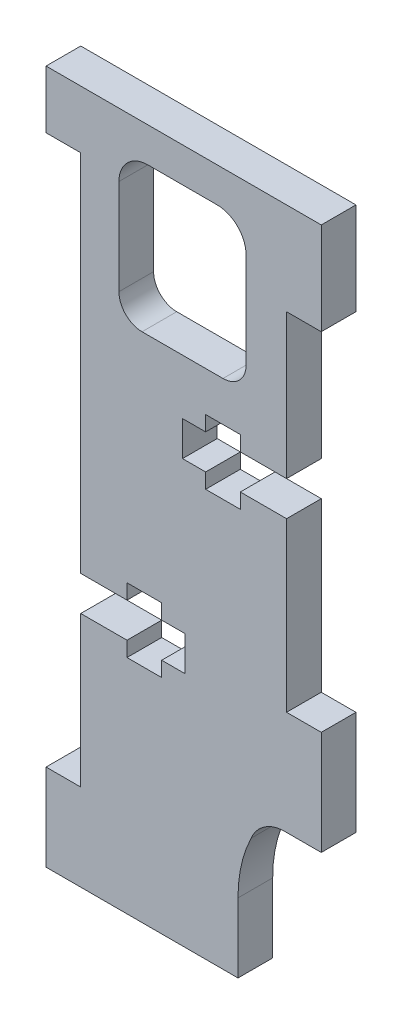
SolidWorks part; units mm, degrees
ref_plane "前基準面" through (0, 0, 0) normal (0, 0, 1) x (1, 0, 0)
ref_plane "上基準面" through (0, 0, 0) normal (0, 1, 0) x (1, 0, 0)
ref_plane "右基準面" through (0, 0, 0) normal (1, 0, 0) x (0, 0, -1)
sketch "草圖1" plane through (0, 0, 0) normal (0, 0, 1) x (1, 0, 0)
  line L0 (284.8002, 84.988) -> (278.8002, 84.988) construction
  line L1 (287.3002, 74.238) -> (287.3002, 82.488) construction
  line L2 (276.3002, 82.488) -> (276.3002, 74.238) construction
  line L3 (278.3002, 72.2381) -> (285.3002, 72.2381) construction
  line L4 (277.0002, 51.488) -> (273.0002, 51.488) construction
  line L5 (277.0002, 52.788) -> (277.0002, 51.488) construction
  line L6 (280.0002, 52.788) -> (277.0002, 52.788) construction
  line L7 (280.0002, 51.488) -> (280.0002, 52.788) construction
  line L8 (282.0002, 51.488) -> (280.0002, 51.488) construction
  line L9 (282.0002, 48.488) -> (282.0002, 51.488) construction
  line L10 (280.0002, 48.488) -> (282.0002, 48.488) construction
  line L11 (280.0002, 47.188) -> (280.0002, 48.488) construction
  line L12 (277.0002, 47.188) -> (280.0002, 47.188) construction
  line L13 (277.0002, 48.488) -> (277.0002, 47.188) construction
  line L14 (273.0002, 48.488) -> (277.0002, 48.488) construction
  line L15 (273.0002, 35.488) -> (273.0002, 48.488) construction
  line L16 (270.0002, 35.488) -> (273.0002, 35.488) construction
  line L17 (286.6002, 27.988) -> (269.9988, 27.988) construction
  line L18 (286.6002, 33.988) -> (286.6002, 27.988) construction
  line L19 (293.8002, 40.988) -> (290.5767, 40.988) construction
  line L20 (293.8002, 49.988) -> (293.8002, 40.988) construction
  line L21 (290.8002, 49.988) -> (293.8002, 49.988) construction
  line L22 (290.8002, 64.488) -> (290.8002, 49.988) construction
  line L23 (286.8002, 64.488) -> (290.8002, 64.488) construction
  line L24 (286.8002, 63.188) -> (286.8002, 64.488) construction
  line L25 (283.8002, 63.188) -> (286.8002, 63.188) construction
  line L26 (283.8002, 64.488) -> (283.8002, 63.188) construction
  line L27 (281.8002, 64.488) -> (283.8002, 64.488) construction
  line L28 (283.8002, 67.488) -> (281.8002, 67.488) construction
  line L29 (281.8002, 67.488) -> (281.8002, 64.488) construction
  line L30 (283.8002, 68.788) -> (283.8002, 67.488) construction
  line L31 (286.8002, 68.788) -> (283.8002, 68.788) construction
  line L32 (286.8002, 67.488) -> (286.8002, 68.788) construction
  line L33 (290.8002, 67.488) -> (286.8002, 67.488) construction
  line L34 (293.8002, 79.988) -> (290.8002, 79.988) construction
  line L35 (290.8002, 79.988) -> (290.8002, 67.488) construction
  line L36 (293.8002, 87.988) -> (293.8002, 79.988) construction
  line L37 (273.0002, 82.988) -> (270.0002, 82.988) construction
  line L38 (270.0002, 82.988) -> (270.0002, 87.988) construction
  line L39 (284.8002, 84.988) -> (278.8002, 84.988)
  line L40 (287.3002, 74.238) -> (287.3002, 82.488)
  line L41 (276.3002, 82.488) -> (276.3002, 74.238)
  line L42 (278.3002, 72.2381) -> (285.3002, 72.2381)
  line L43 (277.0002, 51.488) -> (273.0002, 51.488)
  line L44 (277.0002, 52.788) -> (277.0002, 51.488)
  line L45 (280.0002, 52.788) -> (277.0002, 52.788)
  line L46 (280.0002, 51.488) -> (280.0002, 52.788)
  line L47 (282.0002, 51.488) -> (280.0002, 51.488)
  line L48 (282.0002, 48.488) -> (282.0002, 51.488)
  line L49 (280.0002, 48.488) -> (282.0002, 48.488)
  line L50 (280.0002, 47.188) -> (280.0002, 48.488)
  line L51 (277.0002, 47.188) -> (280.0002, 47.188)
  line L52 (277.0002, 48.488) -> (277.0002, 47.188)
  line L53 (273.0002, 48.488) -> (277.0002, 48.488)
  line L54 (273.0002, 35.488) -> (273.0002, 48.488)
  line L55 (270.0002, 35.488) -> (273.0002, 35.488)
  line L56 (286.6002, 27.988) -> (269.9988, 27.988)
  line L57 (286.6002, 33.988) -> (286.6002, 27.988)
  line L58 (293.8002, 40.988) -> (290.5767, 40.988)
  line L59 (293.8002, 49.988) -> (293.8002, 40.988)
  line L60 (290.8002, 49.988) -> (293.8002, 49.988)
  line L61 (290.8002, 64.488) -> (290.8002, 49.988)
  line L62 (286.8002, 64.488) -> (290.8002, 64.488)
  line L63 (286.8002, 63.188) -> (286.8002, 64.488)
  line L64 (283.8002, 63.188) -> (286.8002, 63.188)
  line L65 (283.8002, 64.488) -> (283.8002, 63.188)
  line L66 (281.8002, 64.488) -> (283.8002, 64.488)
  line L67 (283.8002, 67.488) -> (281.8002, 67.488)
  line L68 (281.8002, 67.488) -> (281.8002, 64.488)
  line L69 (283.8002, 68.788) -> (283.8002, 67.488)
  line L70 (286.8002, 68.788) -> (283.8002, 68.788)
  line L71 (286.8002, 67.488) -> (286.8002, 68.788)
  line L72 (290.8002, 67.488) -> (286.8002, 67.488)
  line L73 (293.8002, 79.988) -> (290.8002, 79.988)
  line L74 (290.8002, 79.988) -> (290.8002, 67.488)
  line L75 (293.8002, 87.988) -> (293.8002, 79.988)
  line L76 (273.0002, 82.988) -> (270.0002, 82.988)
  line L77 (270.0002, 82.988) -> (270.0002, 87.988)
  line L78 (270.0002, 35.488) -> (269.9988, 27.988)
  line L79 (273.0002, 51.488) -> (273.0002, 82.988)
  line L80 (270.0002, 87.988) -> (293.8002, 87.988)
  arc A0 (278.8002, 84.988) -> (276.3002, 82.488) centre (278.8002, 82.488) ccw construction
  arc A1 (287.3002, 82.488) -> (284.8002, 84.988) centre (284.8003, 82.4881) ccw construction
  arc A2 (285.3002, 72.2381) -> (287.3002, 74.238) centre (285.3005, 74.2378) ccw construction
  arc A3 (276.3002, 74.238) -> (278.3002, 72.2381) centre (278.3001, 74.2379) ccw construction
  arc A4 (287.7392, 39.0347) -> (286.6002, 33.988) centre (298.0314, 34.06) ccw construction
  arc A5 (290.5767, 40.988) -> (287.7392, 39.0347) centre (290.6593, 37.8303) ccw construction
  arc A6 (278.8002, 84.988) -> (276.3002, 82.488) centre (278.8002, 82.488) ccw
  arc A7 (287.3002, 82.488) -> (284.8002, 84.988) centre (284.8003, 82.4881) ccw
  arc A8 (285.3002, 72.2381) -> (287.3002, 74.238) centre (285.3005, 74.2378) ccw
  arc A9 (276.3002, 74.238) -> (278.3002, 72.2381) centre (278.3001, 74.2379) ccw
  arc A10 (287.7392, 39.0347) -> (286.6002, 33.988) centre (298.0314, 34.06) ccw
  arc A11 (290.5767, 40.988) -> (287.7392, 39.0347) centre (290.6593, 37.8303) ccw
  point P0 (277.0002, 48.488)
extrude "填料-伸長1" add sketch "草圖1" along normal blind 3
